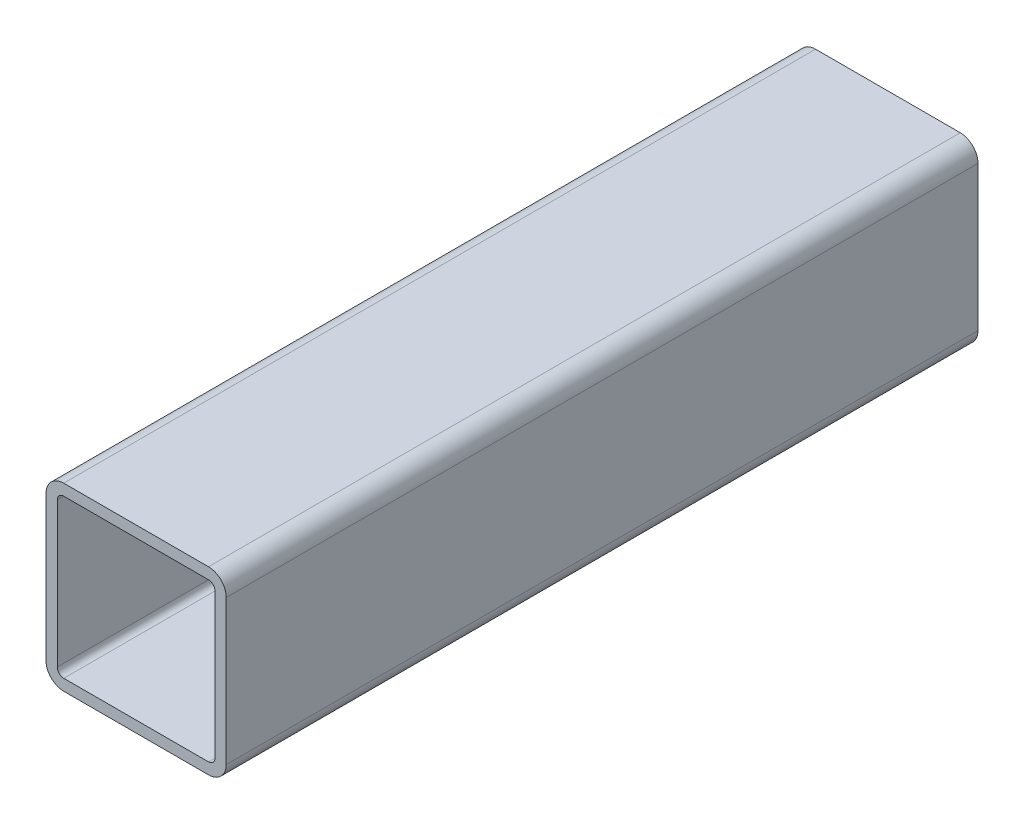
SolidWorks part; units mm, degrees
ref_plane "Front Plane" through (0, 0, 0) normal (0, 0, 1) x (1, 0, 0)
ref_plane "Top Plane" through (0, 0, 0) normal (0, 1, 0) x (1, 0, 0)
ref_plane "Right Plane" through (0, 0, 0) normal (1, 0, 0) x (0, 0, -1)
sketch "Sketch1" plane through (0, 0, 0) normal (0, 0, 1) x (1, 0, 0)
  line L7 (-20.4, 25.4) -> (20.4, 25.4)
  line L8 (25.4, 20.4) -> (25.4, -20.4)
  line L9 (-22.225, 20.4) -> (-22.225, -20.4)
  line L10 (-20.4, -22.225) -> (20.4, -22.225)
  line L11 (20.4, -25.4) -> (-20.4, -25.4)
  line L12 (-25.4, -20.4) -> (-25.4, 20.4)
  line L13 (0, 25.4) -> (0, -25.4) construction
  line L14 (-25.4, 0) -> (25.4, 0) construction
  line L15 (22.225, -20.4) -> (22.225, 20.4)
  line L16 (20.4, 22.225) -> (-20.4, 22.225)
  line L17 (0, 22.225) -> (0, -22.225) construction
  line L18 (-22.225, 0) -> (22.225, 0) construction
  arc A0 (20.4, 25.4) -> (25.4, 20.4) centre (20.4, 20.4) cw
  arc A1 (25.4, -20.4) -> (20.4, -25.4) centre (20.4, -20.4) cw
  arc A2 (-20.4, -25.4) -> (-25.4, -20.4) centre (-20.4, -20.4) cw
  arc A3 (-25.4, 20.4) -> (-20.4, 25.4) centre (-20.4, 20.4) cw
  arc A4 (-22.225, -20.4) -> (-20.4, -22.225) centre (-20.4, -20.4) ccw
  arc A5 (20.4, -22.225) -> (22.225, -20.4) centre (20.4, -20.4) ccw
  arc A6 (22.225, 20.4) -> (20.4, 22.225) centre (20.4, 20.4) ccw
  arc A7 (-20.4, 22.225) -> (-22.225, 20.4) centre (-20.4, 20.4) ccw
  point P39 (0, 0)
  dimension "D1" = 5
  dimension "D2" = 50.8
  dimension "D3" = 3.175
extrude "Boss-Extrude1" add sketch "Sketch1" along normal blind 211.9
